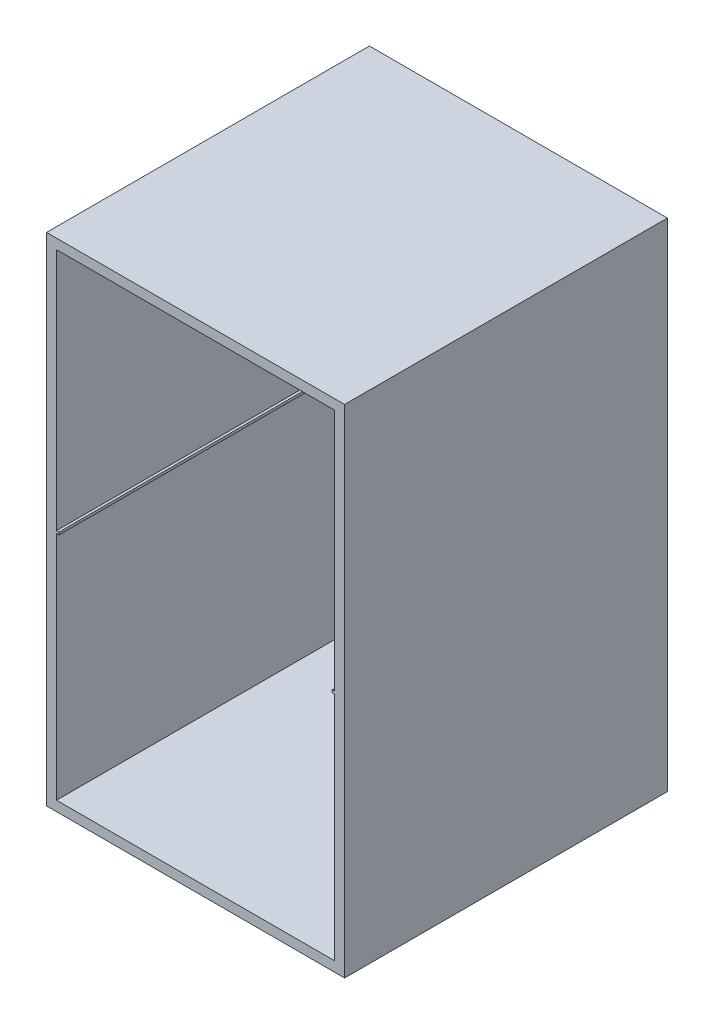
SolidWorks part; units mm, degrees
ref_plane "Front Plane" through (0, 0, 0) normal (0, 0, 1) x (1, 0, 0)
ref_plane "Top Plane" through (0, 0, 0) normal (0, 1, 0) x (1, 0, 0)
ref_plane "Right Plane" through (0, 0, 0) normal (1, 0, 0) x (0, 0, -1)
sketch "Sketch1" plane through (0, 0, 0) normal (0, 0, 1) x (1, 0, 0)
  line L1 (300, -500) -> (-300, -500)
  line L2 (300, -500) -> (300, 500)
  line L3 (300, 500) -> (-300, 500)
  line L4 (-300, -500) -> (-300, 500)
  line L5 (300, -500) -> (-300, 500) construction
  line L6 (300, 500) -> (-300, -500) construction
  point P0 (0, 0)
  dimension "D1" = 600
  dimension "D2" = 1000
extrude "Boss-Extrude1" add sketch "Sketch1" along normal blind 650
shell "Shell1" thickness 20
sketch "Sketch2" plane through (0, 0, 650) normal (0, 0, 1) x (1, 0, 0)
  line L0 (280, 10) -> (-280, 10)
  line L1 (280, -480) -> (280, 480) construction
  line L2 (-280, 480) -> (-280, -480) construction
  line L3 (280, 480) -> (-280, 480) construction
  line L4 (-280, -480) -> (280, -480) construction
  line L5 (280, 10) -> (-280, 10)
  line L6 (280, 10) -> (280, -10)
  line L7 (280, -10) -> (-280, -10)
  line L8 (-280, 10) -> (-280, -10)
  line L9 (0, -55) -> (0, 55) construction
  line L10 (280, -10) -> (275, -10)
  line L11 (280, -10) -> (280, -15)
  line L12 (280, -15) -> (275, -15)
  line L13 (275, -10) -> (275, -15)
  line L14 (-280, -15) -> (-275, -15)
  line L15 (-275, -10) -> (-275, -15)
  line M6 (-280, -480) -> (-280, 480)
  line M8 (280, 480) -> (280, -480)
  dimension "D1" = 470
  dimension "D2" = 20
  dimension "D3" = 470
  dimension "D4" = 5
  dimension "D5" = 5
extrude "Boss-Extrude2" add sketch "Sketch2" against normal up to next contours L15 L7 L14 M6 | L7 L13 L12 M8
